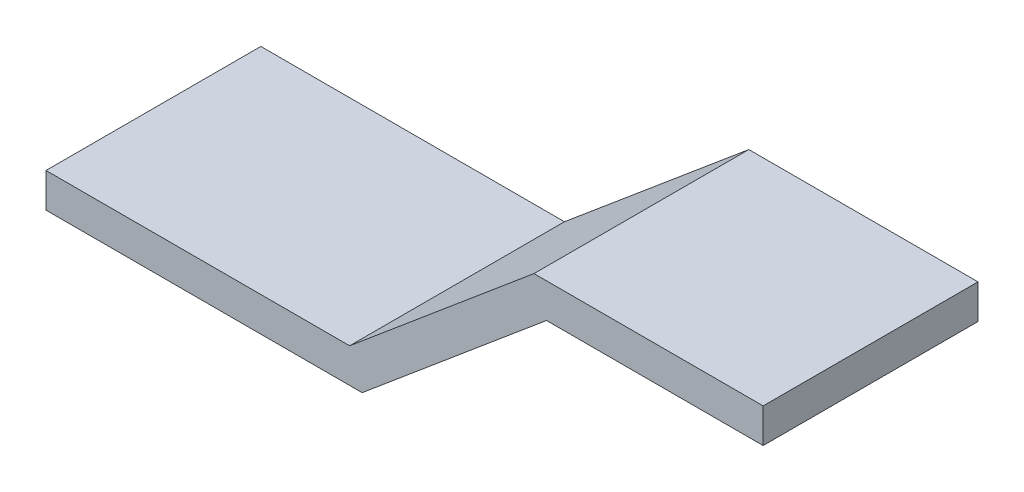
SolidWorks part; units mm, degrees
ref_plane "Alzado" through (0, 0, 0) normal (0, 0, 1) x (1, 0, 0)
ref_plane "Planta" through (0, 0, 0) normal (0, 1, 0) x (1, 0, 0)
ref_plane "Vista lateral" through (0, 0, 0) normal (1, 0, 0) x (0, 0, -1)
sketch "Croquis1" plane through (0, 0, 0) normal (0, 0, 1) x (1, 0, 0)
  line L0 (0, 85.1318) -> (0, -85.1318) construction
  line L1 (-114.1524, 0) -> (114.1524, 0) construction
  line L2 (186.553, 54) -> (106.553, 54)
  line L3 (106.553, 54) -> (42.1983, 0)
  line L4 (42.1983, 0) -> (-63.8017, 0)
  line L10 (186.553, 42) -> (110.9207, 42)
  line L11 (110.9207, 42) -> (46.566, -12)
  line L12 (46.566, -12) -> (-63.8017, -12)
  line L13 (186.553, 54) -> (186.553, 42)
  line L14 (-63.8017, 0) -> (-63.8017, -12)
  point P5 (0, 0)
  point P6 (0, 0)
  dimension "D1" = 80
  dimension "D2" = 54
  dimension "D3" = 140
  dimension "D4" = 12
extrude "Saliente-Extruir1" add sketch "Croquis1" along normal mid plane 75
